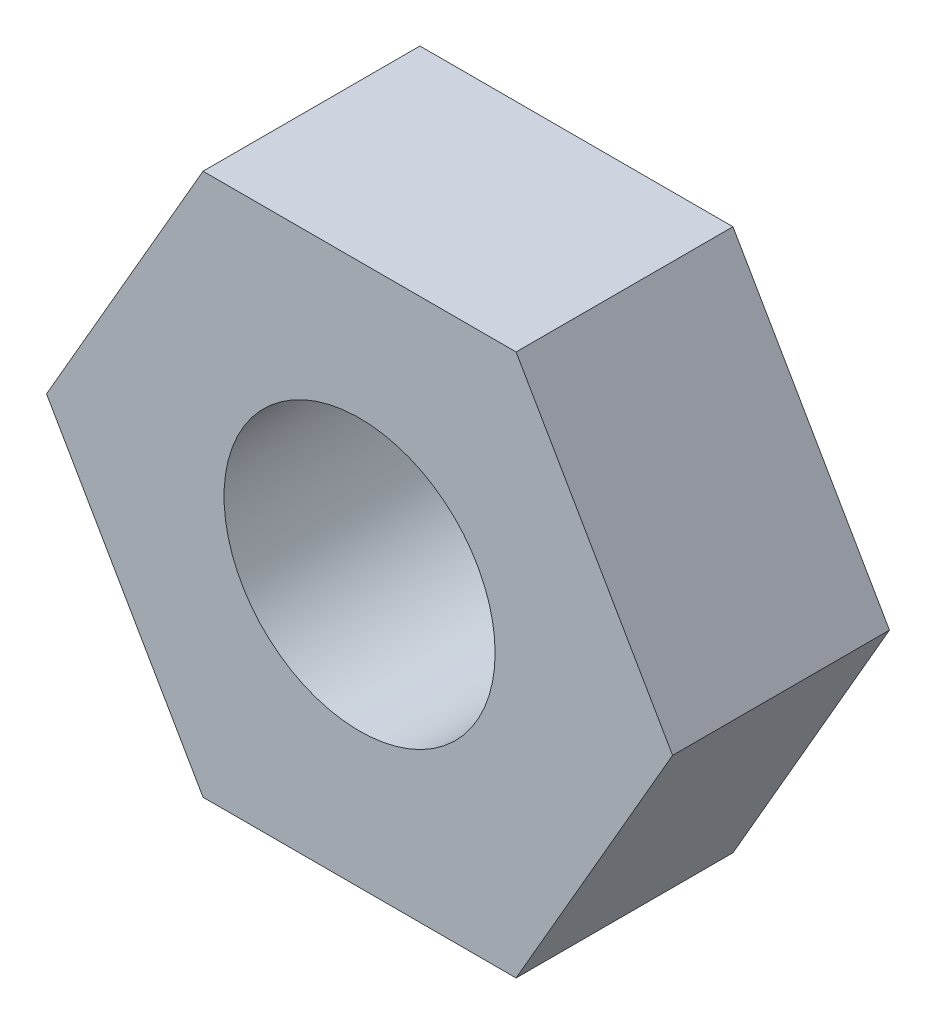
SolidWorks part; units mm, degrees
ref_plane "前视基准面" through (0, 0, 0) normal (0, 0, 1) x (1, 0, 0)
ref_plane "上视基准面" through (0, 0, 0) normal (0, 1, 0) x (1, 0, 0)
ref_plane "右视基准面" through (0, 0, 0) normal (1, 0, 0) x (0, 0, -1)
other "Configuration Table"
sketch "草图1" plane through (0, 0, 0) normal (0, 0, 1) x (1, 0, 0)
  line L0 (2.3094, 0) -> (1.1547, 2)
  line L1 (1.1547, 2) -> (-1.1547, 2)
  line L2 (-1.1547, 2) -> (-2.3094, 0)
  line L3 (-2.3094, 0) -> (-1.1547, -2)
  line L4 (-1.1547, -2) -> (1.1547, -2)
  line L5 (1.1547, -2) -> (2.3094, 0)
  circle A0 centre (0, 0) radius 1
extrude "标准对边_厚度_螺纹孔" add sketch "草图1" along normal blind 1.6
